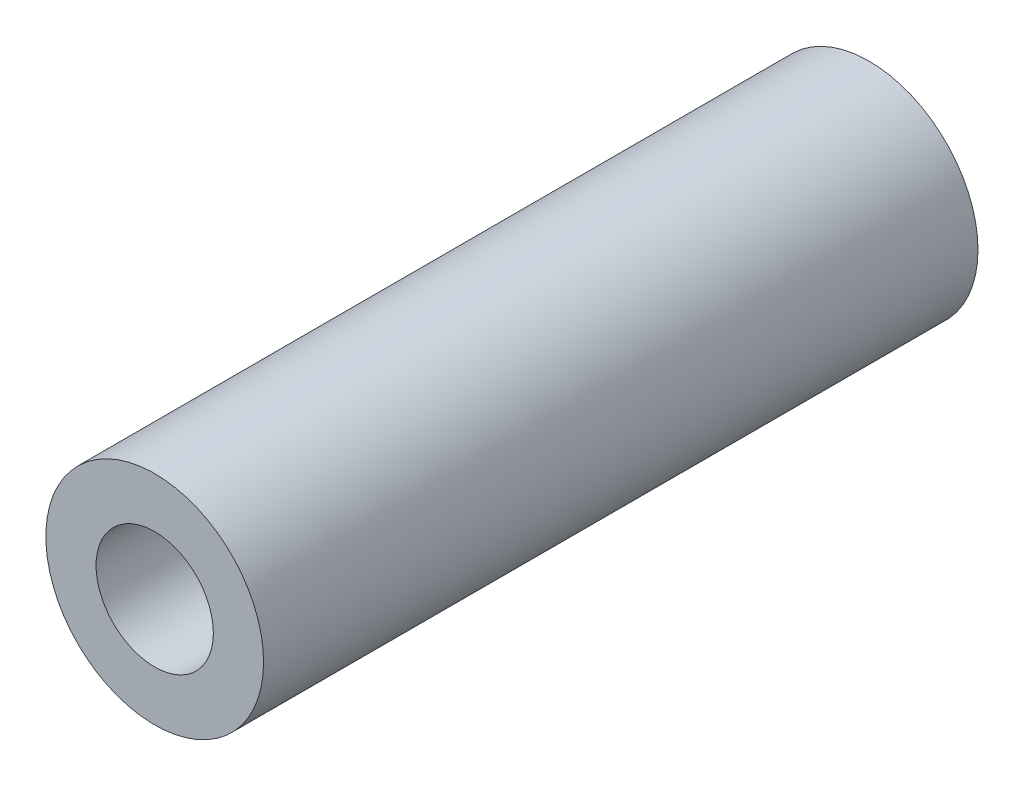
SolidWorks part; units mm, degrees
material "PBT General Purpose"
ref_plane "Front Plane" through (0, 0, 0) normal (0, 0, 1) x (1, 0, 0)
ref_plane "Top Plane" through (0, 0, 0) normal (0, 1, 0) x (1, 0, 0)
ref_plane "Right Plane" through (0, 0, 0) normal (1, 0, 0) x (0, 0, -1)
sketch "Sketch2" plane through (0, 0, 0) normal (0, 0, 1) x (1, 0, 0)
  circle A0 centre (0, 0) radius 2.5654
  circle A1 centre (0, 0) radius 4.7625
  dimension "D1" = 5.1308
  dimension "D2" = 9.525
extrude "Boss-Extrude1" add sketch "Sketch2" along normal blind 31.2547
